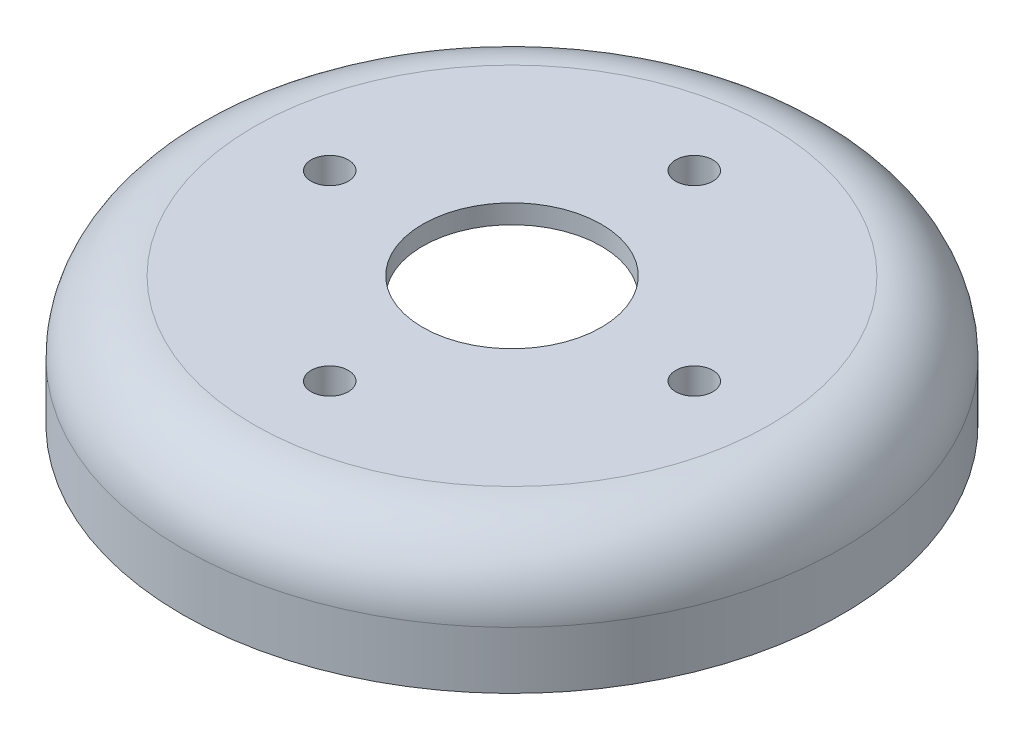
SolidWorks part; units mm, degrees
ref_plane "Front Plane" through (0, 0, 0) normal (0, 0, 1) x (1, 0, 0)
ref_plane "Top Plane" through (0, 0, 0) normal (0, 1, 0) x (1, 0, 0)
ref_plane "Right Plane" through (0, 0, 0) normal (1, 0, 0) x (0, 0, -1)
sketch "Sketch1" plane through (0, 0, 0) normal (0, 0, 1) x (1, 0, 0)
  line L0 (0, 0) -> (41.1, 0) construction
  line L7 (0, 41) -> (0, 43)
  line L8 (0, 43) -> (46.1, 43)
  line L9 (46.1, 43) -> (46.1, 25)
  line L10 (46.1, 25) -> (44.1, 25)
  line L11 (0, 41) -> (0, 69.4201) construction
  ellipse E0 centre (0, 25) end of major axis (44.1, 25) minor radius 16 (0, 41) -> (44.1, 25) cw
  dimension "D1" = 41.1
  dimension "D5" = 16
  dimension "D7" = 2
  dimension "D8" = 2
sketch "Sketch2" plane through (0, 0, 0) normal (0, 1, 0) x (1, 0, 0)
  line L0 (0, -25.5) -> (0, 25.5) construction
  line L1 (25.5, 0) -> (-25.5, 0) construction
  circle A0 centre (0, 0) radius 25.5 construction
  circle A1 centre (25.5, 0) radius 2.6
  circle A2 centre (0, -25.5) radius 2.6
  circle A3 centre (-25.5, 0) radius 2.6
  circle A4 centre (0, 25.5) radius 2.6
  circle A5 centre (0, 0) radius 12.5
  point P17 (0, 0)
  dimension "D1" = 51
  dimension "D2" = 5.2
  dimension "D4" = 25
  dimension "D3" = 4
revolve "Revolve1" add sketch "Sketch1" angle 360 about L11
extrude "Cut-Extrude1" cut sketch "Sketch2" along normal through all
fillet "Fillet1" radius 10 1 edges at (0, 43, -46.1)
